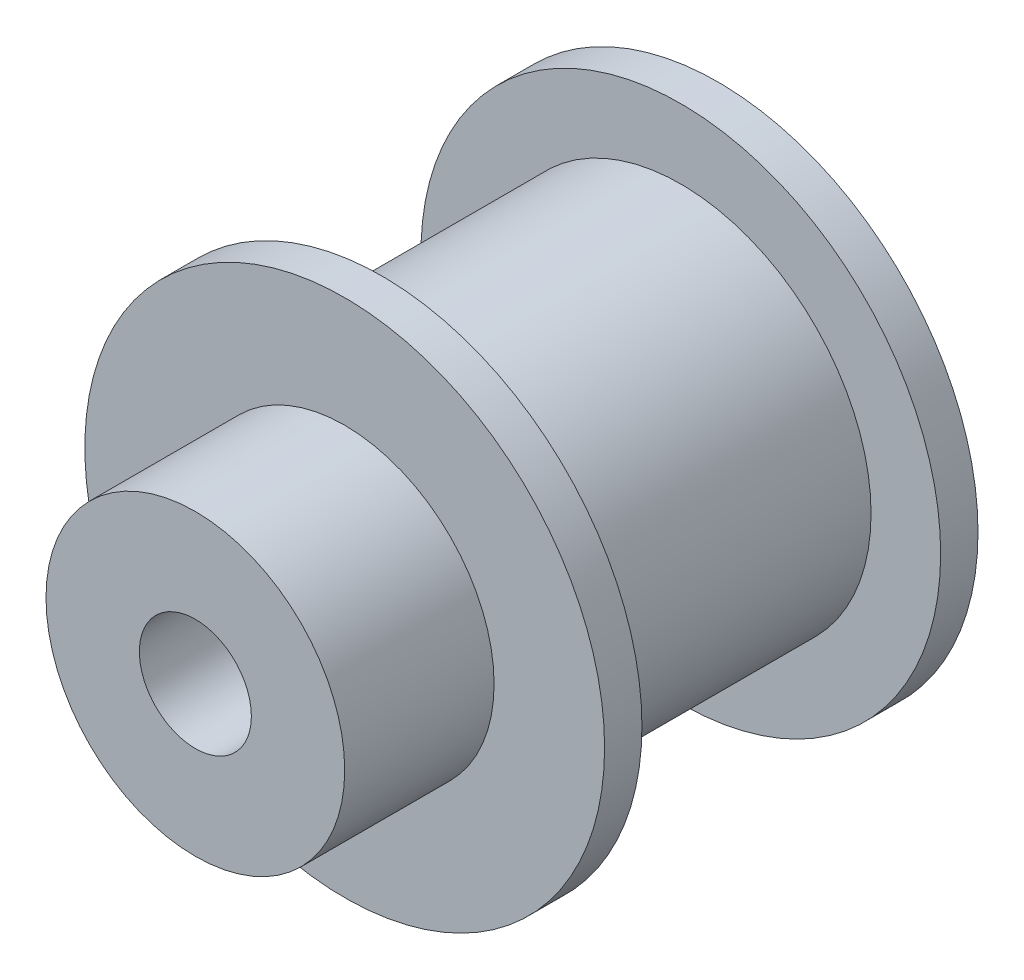
SolidWorks part; units mm, degrees
ref_plane "Front Plane" through (0, 0, 0) normal (0, 0, 1) x (1, 0, 0)
ref_plane "Top Plane" through (0, 0, 0) normal (0, 1, 0) x (1, 0, 0)
ref_plane "Right Plane" through (0, 0, 0) normal (1, 0, 0) x (0, 0, -1)
sketch "Sketch1" plane through (0, 0, 0) normal (0, 0, 1) x (1, 0, 0)
  circle A0 centre (0, 0) radius 11.049
extrude "Boss-Extrude1" add sketch "Sketch1" along normal blind 1.5875
sketch "Sketch2" plane through (0, 0, 1.5875) normal (0, 0, 1) x (1, 0, 0)
  circle A0 centre (0, 0) radius 8.0899
extrude "Boss-Extrude2" add sketch "Sketch2" along normal blind 12.7
sketch "Sketch3" plane through (0, 0, 14.2875) normal (0, 0, 1) x (1, 0, 0)
  circle A0 centre (0, 0) radius 11.049
extrude "Boss-Extrude3" add sketch "Sketch3" along normal blind 1.5875
sketch "Sketch4" plane through (0, 0, 15.875) normal (0, 0, 1) x (1, 0, 0)
  circle A0 centre (0, 0) radius 6.35
extrude "Boss-Extrude4" add sketch "Sketch4" along normal blind 6.35
sketch "Sketch5" plane through (0, 0, 22.225) normal (0, 0, 1) x (1, 0, 0)
  circle A0 centre (0, 0) radius 2.3813
extrude "Cut-Extrude1" cut sketch "Sketch5" against normal blind 25.4
